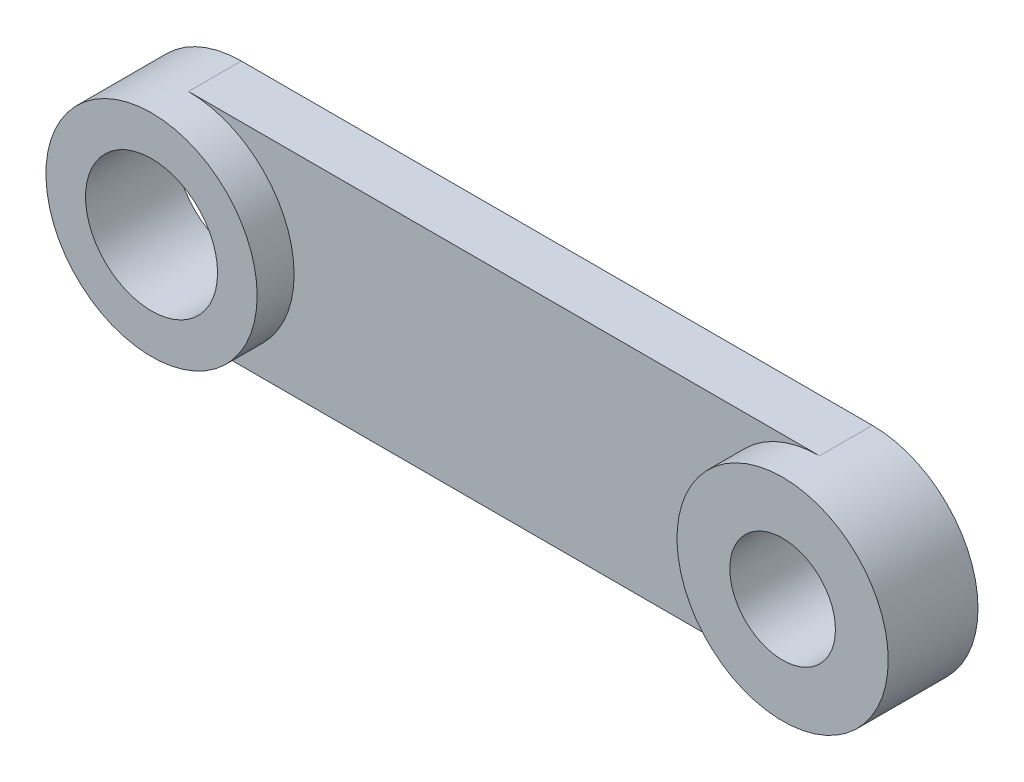
SolidWorks part; units mm, degrees
ref_plane "Piano frontale" through (0, 0, 0) normal (0, 0, 1) x (1, 0, 0)
ref_plane "Piano superiore" through (0, 0, 0) normal (0, 1, 0) x (1, 0, 0)
ref_plane "Piano destro" through (0, 0, 0) normal (1, 0, 0) x (0, 0, -1)
sketch "Schizzo1" plane through (0, 0, 0) normal (0, 0, 1) x (1, 0, 0)
  line L1 (-59.75, -20) -> (59.75, -20)
  line L2 (-59.75, -20) -> (-59.75, 20)
  line L3 (-59.75, 20) -> (59.75, 20)
  line L4 (59.75, -20) -> (59.75, 20)
  line L5 (-59.75, -20) -> (59.75, 20) construction
  line L6 (-59.75, 20) -> (59.75, -20) construction
  point P0 (0, 0)
  dimension "D1" = 119.5
  dimension "D2" = 40
extrude "Estrusione-Estrusione1" add sketch "Schizzo1" along normal blind 10
sketch "Schizzo2" plane through (0, 0, 0) normal (0, 0, 1) x (1, 0, 0)
  line L0 (59.75, -20) -> (59.75, 20) construction
  line L1 (-59.75, 20) -> (-59.75, -20) construction
  circle A0 centre (59.75, 0) radius 20
  circle A1 centre (-59.75, 0) radius 20
extrude "Estrusione-Estrusione2" add sketch "Schizzo2" along normal blind 17
sketch "Schizzo3" plane through (0, 0, 0) normal (0, 0, 1) x (1, 0, 0)
  circle A0 centre (-59.75, 0) radius 12.5
  circle A1 centre (59.75, 0) radius 10
  dimension "D1" = 25
  dimension "D2" = 20
extrude "Taglio-Estrusione2" cut sketch "Schizzo3" along normal through all contours A0 | A1
